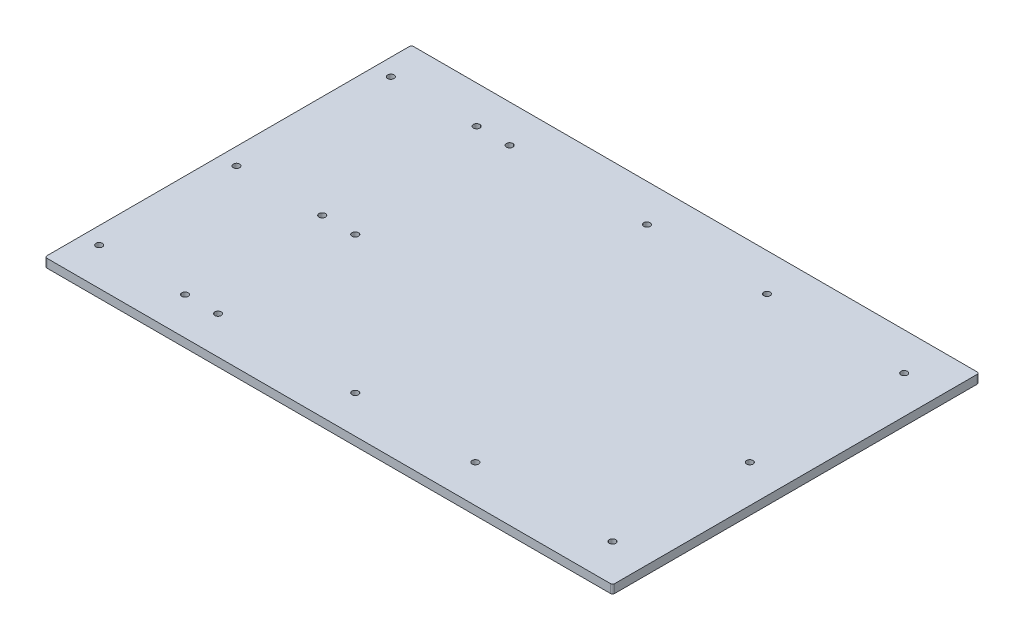
SolidWorks part; units mm, degrees
material "PVC Rigid"
ref_plane "Front Plane" through (0, 0, 0) normal (0, 0, 1) x (1, 0, 0)
ref_plane "Top Plane" through (0, 0, 0) normal (0, 1, 0) x (1, 0, 0)
ref_plane "Right Plane" through (0, 0, 0) normal (1, 0, 0) x (0, 0, -1)
sketch "Sketch1" plane through (0, 0, 0) normal (0, 1, 0) x (1, 0, 0)
  line L0 (-420.37, 268.2875) -> (-420.37, -268.2875)
  line L1 (-417.195, -271.4625) -> (417.195, -271.4625)
  line L2 (420.37, -268.2875) -> (420.37, 268.2875)
  line L3 (417.195, 271.4625) -> (-417.195, 271.4625)
  line L4 (-420.37, 0) -> (420.37, 0) construction
  circle A0 centre (-16.1925, -215.9) radius 4.7625
  circle A5 centre (161.6075, -215.9) radius 4.7625
  circle A6 centre (161.6075, 215.9) radius 4.7625
  circle A7 centre (-16.1925, 215.9) radius 4.7625
  circle A8 centre (-268.2875, -215.9) radius 4.7625
  circle A9 centre (-395.2875, -215.9) radius 4.7625
  circle A10 centre (-268.2875, 215.9) radius 4.7625
  circle A11 centre (-395.2875, 215.9) radius 4.7625
  circle A12 centre (364.8075, -215.9) radius 4.7625
  circle A13 centre (-219.3925, -215.9) radius 4.7625
  circle A14 centre (364.8075, 215.9) radius 4.7625
  circle A15 centre (-219.3925, 215.9) radius 4.7625
  arc A16 (-420.37, -268.2875) -> (-417.195, -271.4625) centre (-417.195, -268.2875) ccw
  arc A17 (417.195, -271.4625) -> (420.37, -268.2875) centre (417.195, -268.2875) ccw
  arc A18 (420.37, 268.2875) -> (417.195, 271.4625) centre (417.195, 268.2875) ccw
  arc A19 (-417.195, 271.4625) -> (-420.37, 268.2875) centre (-417.195, 268.2875) ccw
  circle A20 centre (-219.3925, -12.7) radius 4.7625
  circle A21 centre (364.8075, -12.7) radius 4.7625
  circle A22 centre (-395.2875, -12.7) radius 4.7625
  circle A23 centre (-268.2875, -12.7) radius 4.7625
extrude "Boss-Extrude1" add sketch "Sketch1" along normal blind 12.7
